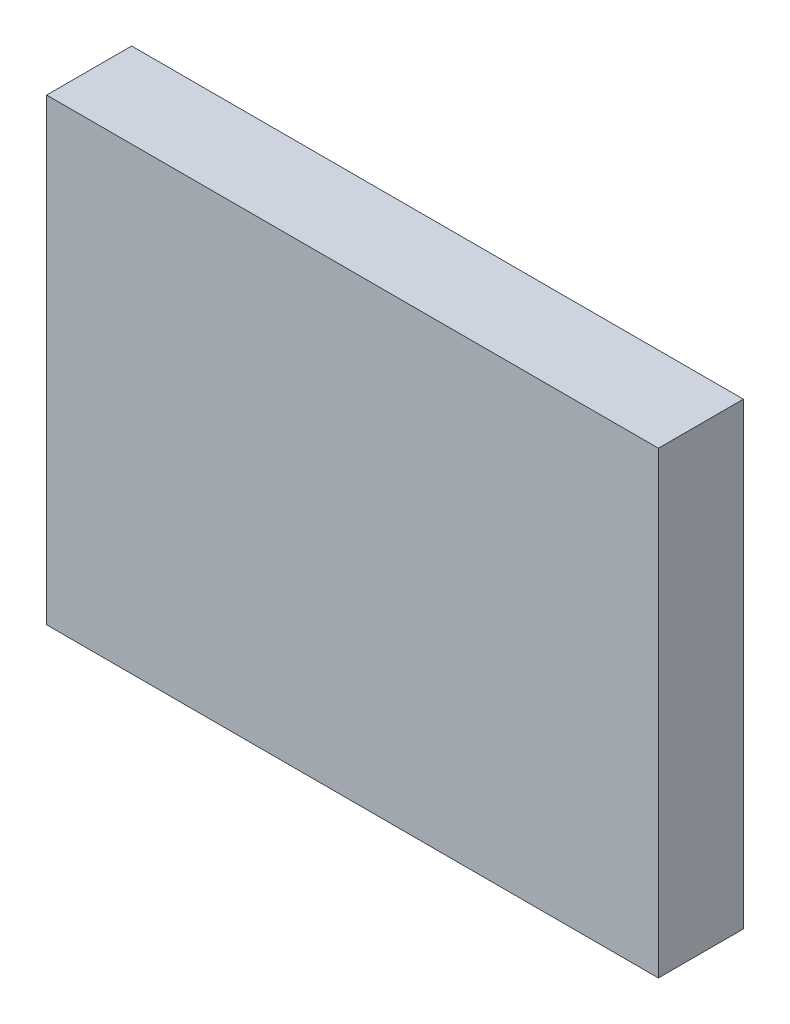
SolidWorks part; units mm, degrees
ref_plane "Спереди" through (0, 0, 0) normal (0, 0, 1) x (1, 0, 0)
ref_plane "Сверху" through (0, 0, 0) normal (0, 1, 0) x (1, 0, 0)
ref_plane "Справа" through (0, 0, 0) normal (1, 0, 0) x (0, 0, -1)
sketch "Эскиз1" plane through (0, 0, 0) normal (0, 0, 1) x (1, 0, 0)
  line L1 (-180, 135) -> (180, 135)
  line L2 (-180, 135) -> (-180, -135)
  line L3 (-180, -135) -> (180, -135)
  line L4 (180, 135) -> (180, -135)
  line L5 (-180, 135) -> (180, -135) construction
  line L6 (-180, -135) -> (180, 135) construction
  point P0 (0, 0)
extrude "Бобышка-Вытянуть1" add sketch "Эскиз1" along normal blind 50
